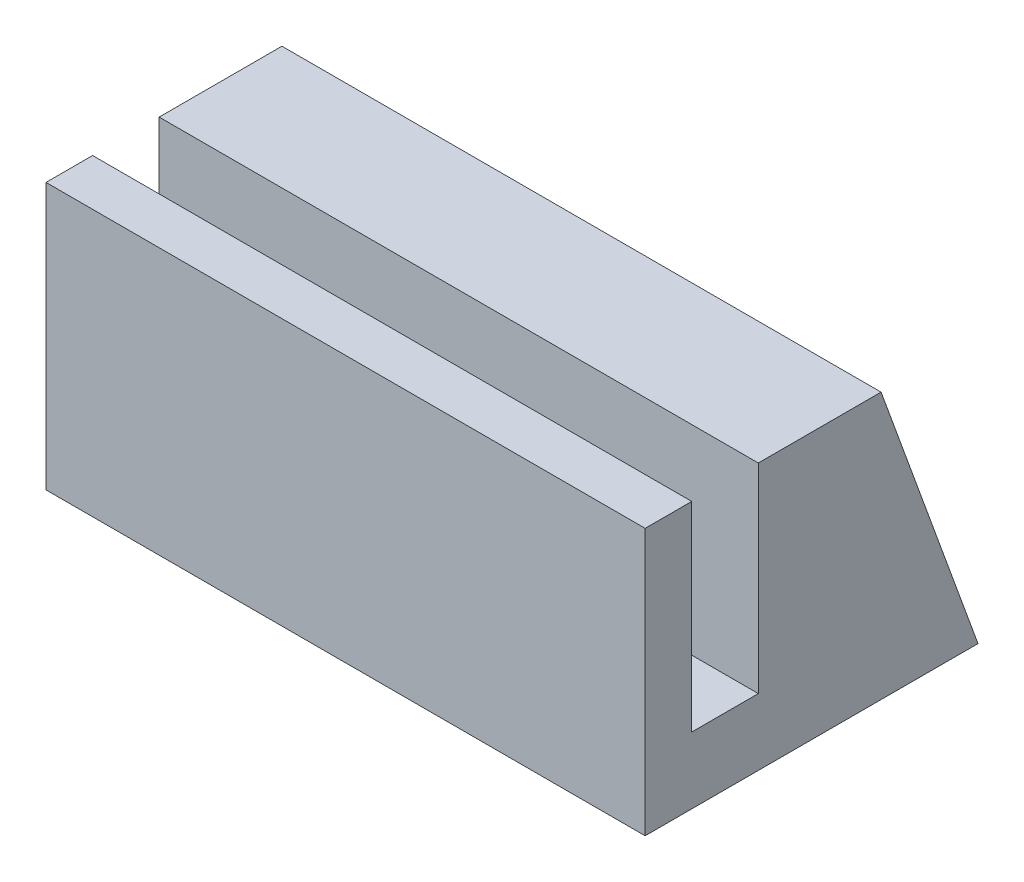
SolidWorks part; units mm, degrees
ref_plane "Front Plane" through (0, 0, 0) normal (0, 0, 1) x (1, 0, 0)
ref_plane "Top Plane" through (0, 0, 0) normal (0, 1, 0) x (1, 0, 0)
ref_plane "Right Plane" through (0, 0, 0) normal (1, 0, 0) x (0, 0, -1)
sketch "Sketch2" plane through (0, 0, 0) normal (0, 0, 1) x (1, 0, 0)
  line L1 (-22.5, -10) -> (22.5, -10)
  line L2 (-22.5, -10) -> (-22.5, 10)
  line L3 (-22.5, 10) -> (22.5, 10)
  line L4 (22.5, -10) -> (22.5, 10)
  line L5 (-22.5, -10) -> (22.5, 10) construction
  line L6 (-22.5, 10) -> (22.5, -10) construction
  point P0 (0, 0)
  dimension "D1" = 45
  dimension "D2" = 20
extrude "Boss-Extrude1" add sketch "Sketch2" along normal blind 25
sketch "Sketch5" plane through (0, 10, 0) normal (0, 1, 0) x (1, 0, 0)
  line L0 (0, 0) -> (0, -15)
  line L1 (0, -15) -> (0, -19)
  line L2 (22.5, -25) -> (22.5, 0) construction
  line L3 (-22.5, -16.5) -> (22.5, -16.5)
  line L4 (-22.5, -16.5) -> (-22.5, -21.5)
  line L5 (-22.5, -21.5) -> (22.5, -21.5)
  line L6 (22.5, -16.5) -> (22.5, -21.5)
  line L7 (-22.5, -16.5) -> (22.5, -21.5) construction
  line L8 (-22.5, -21.5) -> (22.5, -16.5) construction
  dimension "D1" = 15
  dimension "D2" = 4
  dimension "D3" = 5
extrude "Cut-Extrude1" cut sketch "Sketch5" against normal blind 15
sketch "Sketch7" plane through (22.5, 0, 0) normal (1, 0, 0) x (0, 0, -1)
  line L0 (0, -10) -> (0, 10)
  line L1 (0, 10) -> (-7.28, 10)
  line L2 (-16.5, 10) -> (0, 10) construction
  line L3 (-7.28, 10) -> (0, -10)
  dimension "D1" = 7.28
extrude "Cut-Extrude2" cut sketch "Sketch7" against normal up to surface (45 mm away) up to face at (-22.5, 1.25, 15.75)
sketch "Sketch8" plane through (0, -1.1699, 3.2141) normal (0, 0.342, -0.9397) x (-1, 0, 0)
  line L1 (-19.15, -4.8) -> (19.15, -4.8)
  line L2 (-19.15, -4.8) -> (-19.15, 4.8)
  line L3 (-19.15, 4.8) -> (19.15, 4.8)
  line L4 (19.15, -4.8) -> (19.15, 4.8)
  line L5 (-19.15, -4.8) -> (19.15, 4.8) construction
  line L6 (-19.15, 4.8) -> (19.15, -4.8) construction
  point P0 (0, 0)
  dimension "D1" = 38.3
  dimension "D2" = 9.6
extrude "Cut-Extrude3" cut sketch "Sketch8" against normal blind 10
